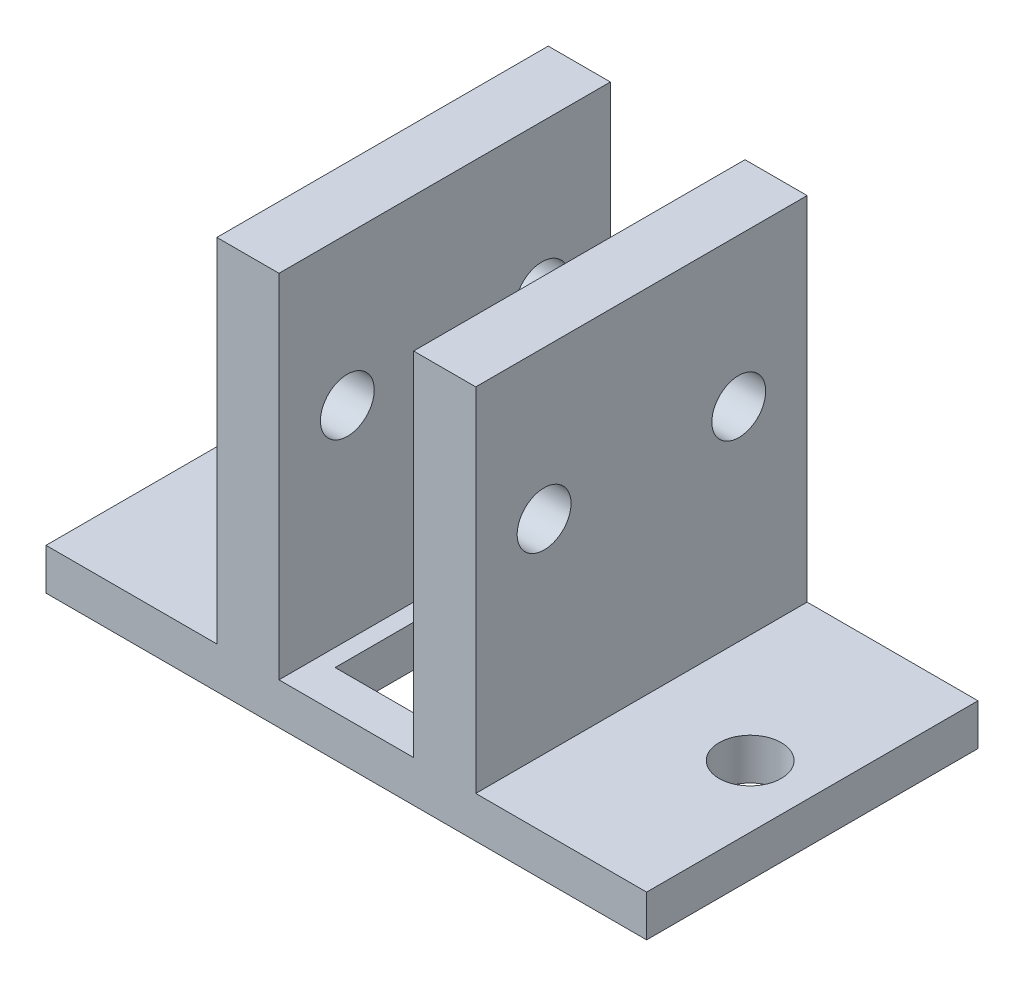
SolidWorks part; units mm, degrees
ref_plane "Alzado" through (0, 0, 0) normal (0, 0, 1) x (1, 0, 0)
ref_plane "Planta" through (0, 0, 0) normal (0, 1, 0) x (1, 0, 0)
ref_plane "Vista lateral" through (0, 0, 0) normal (1, 0, 0) x (0, 0, -1)
sketch "Croquis1" plane through (0, 0, 0) normal (0, 1, 0) x (1, 0, 0)
  line L0 (14.5, 8) -> (14.5, 0) construction
  line L2 (14.5, -8) -> (14.5, 8)
  line L3 (14.5, 8) -> (-14.5, 8)
  line L4 (-14.5, -8) -> (-14.5, 8)
  line L5 (14.5, -8) -> (-14.5, 8) construction
  line L6 (14.5, 8) -> (-14.5, -8) construction
  line L7 (14.5, 0) -> (11.5, 0) construction
  line L8 (0, 8) -> (0, -8) construction
  line L9 (-14.5, -8) -> (14.5, -8)
  line L10 (0, -8) -> (10, -8) construction
  line L14 (-10, -8) -> (-4.75, -8) construction
  circle A0 centre (11.5, 0) radius 1.5
  circle A1 centre (-11.5, 0) radius 1.5
  point P0 (0, 0)
  dimension "D3" = 3
  dimension "D1" = 29
  dimension "D2" = 16
extrude "Saliente-Extruir1" add sketch "Croquis1" along normal blind 2
sketch "Croquis2" plane through (0, 2, 0) normal (0, 1, 0) x (1, 0, 0)
  line L0 (6.25, -8) -> (6.25, 8)
  line L1 (14.5, 8) -> (-14.5, 8) construction
  line L2 (-3.25, 8) -> (-3.25, -8)
  line L3 (-14.5, -8) -> (14.5, -8) construction
  line L4 (-3.25, -8) -> (-6.25, -8)
  line L5 (-6.25, -8) -> (-6.25, 8)
  line L6 (-6.25, 8) -> (-3.25, 8)
  line L7 (0, 8) -> (0, -8) construction
  line L8 (3.25, -8) -> (6.25, -8)
  line L9 (3.25, 8) -> (3.25, -8)
  line L10 (6.25, 8) -> (3.25, 8)
  dimension "D1" = 3
extrude "Saliente-Extruir2" add sketch "Croquis2" along normal blind 17
sketch "Croquis3" plane through (6.25, 0, 0) normal (1, 0, 0) x (0, 0, -1)
  line L0 (-8, 19) -> (-10, 19) construction
  line L1 (-10, 19) -> (10, 19) construction
  line L2 (10, 19) -> (10, 9) construction
  line L3 (-10, 9) -> (10.1921, 9) construction
  line L4 (-10, 9) -> (-10, 19) construction
  line L5 (-10, 9) -> (-4.7, 9) construction
  line L6 (-4.7, 9) -> (-4.7, 11.8297) construction
  line L7 (0, 9) -> (0, 19) construction
  line L8 (-4.7, 11.8297) -> (-10, 11.8297) construction
  circle A0 centre (-4.7, 11.8297) radius 1.3
  circle A1 centre (4.7, 11.8297) radius 1.3
  dimension "D1" = 2.6
extrude "Cortar-Extruir1" cut sketch "Croquis3" against normal blind 17
sketch "Croquis4" plane through (0, 2, 0) normal (0, 1, 0) x (1, 0, 0)
  line L1 (2.4092, -6.1312) -> (-2.4092, -6.1312)
  line L2 (2.4092, -6.1312) -> (2.4092, 6.1312)
  line L3 (2.4092, 6.1312) -> (-2.4092, 6.1312)
  line L4 (-2.4092, -6.1312) -> (-2.4092, 6.1312)
  line L5 (2.4092, -6.1312) -> (-2.4092, 6.1312) construction
  line L6 (2.4092, 6.1312) -> (-2.4092, -6.1312) construction
  point P0 (0, 0)
extrude "Cortar-Extruir2" cut sketch "Croquis4" against normal blind 10
